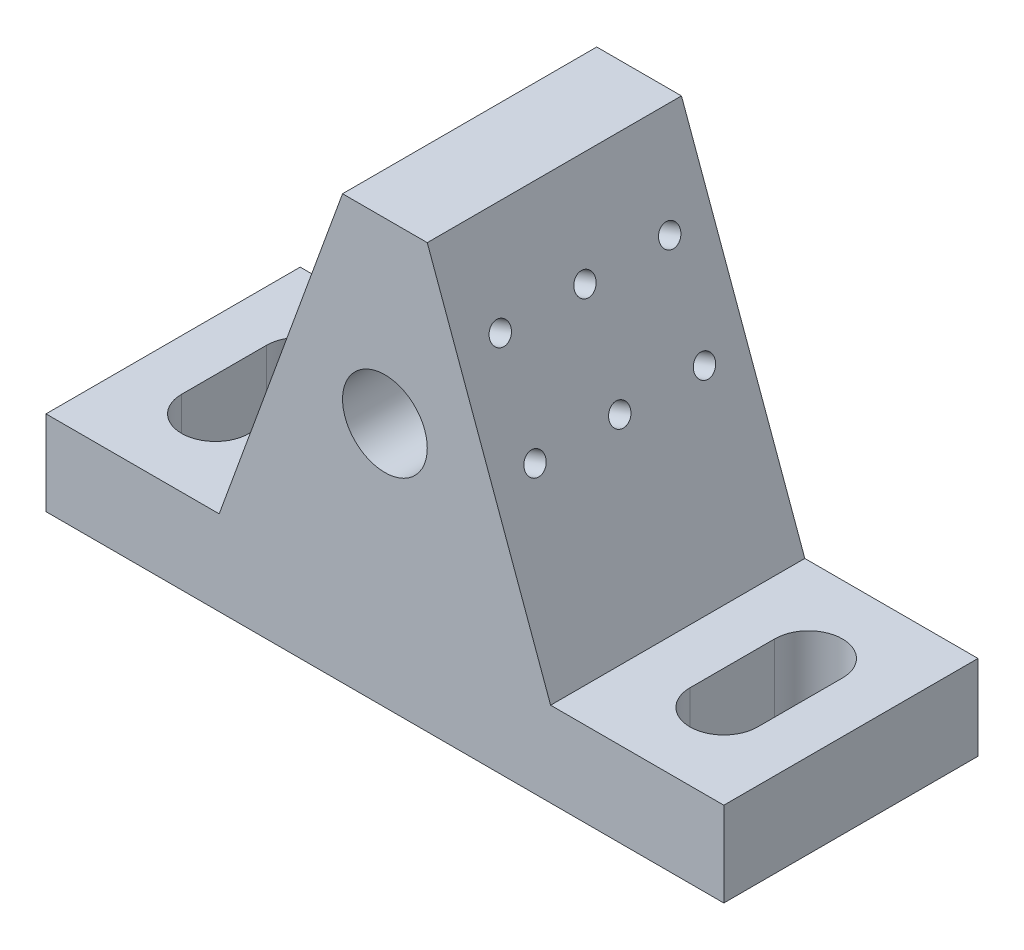
SolidWorks part; units mm, degrees
material "AISI 304"
ref_plane "Front Plane" through (0, 0, 0) normal (0, 0, 1) x (1, 0, 0)
ref_plane "Top Plane" through (0, 0, 0) normal (0, 1, 0) x (1, 0, 0)
ref_plane "Right Plane" through (0, 0, 0) normal (1, 0, 0) x (0, 0, -1)
sketch "Sketch2" plane through (0, 0, 0) normal (0, 0, 1) x (1, 0, 0)
  line L0 (0, 0) -> (0, 50) construction
  line L1 (-40, 0) -> (40, 0)
  line L2 (40, 0) -> (40, 10)
  line L3 (40, 10) -> (19.5588, 10)
  line L4 (19.5588, 10) -> (5, 50)
  line L5 (5, 50) -> (-5, 50)
  line L6 (-19.5588, 10) -> (-5, 50)
  line L7 (-40, 10) -> (-19.5588, 10)
  line L8 (-40, 0) -> (-40, 10)
  dimension "D1" = 10
  dimension "D2" = 10
  dimension "D3" = 110
  dimension "D4" = 80
  dimension "D5" = 50
extrude "Base Extrude" add sketch "Sketch2" along normal mid plane 30
sketch "Sketch4" plane through (0, 0, 0) normal (0, 1, 0) x (1, 0, 0)
  line L0 (30, -5) -> (30, 5) construction
  line L1 (26, -5) -> (26, 5)
  line L2 (34, -5) -> (34, 5)
  line L3 (40, 15) -> (19.5588, 15) construction
  arc A0 (26, -5) -> (34, -5) centre (30, -5) ccw
  arc A1 (34, 5) -> (26, 5) centre (30, 5) ccw
  point P2 (30, 0)
  dimension "D4" = 4
  dimension "D1" = 10
  dimension "D2" = 30
  dimension "D3" = 10
extrude "Slot Cut" cut sketch "Sketch4" along normal through all
mirror "Mirror1" about plane through (0, 0, 0) normal (1, 0, 0) of "Slot Cut"
sketch "Sketch5" plane through (0, 0, 15) normal (0, 0, 1) x (1, 0, 0)
  circle A0 centre (0, 29) radius 5
  dimension "D1" = 10
  dimension "D2" = 29
extrude "Guide Hole" cut sketch "Sketch5" against normal through all
hole_wizard "M3x0.5 Tapped Hole2" positions "3DSketch1" profile "Sketch10" tap size "M3x0.5" standard "ANSI Metric"
sketch3d "3DSketch1"
  line L0 (19.5588, 10, -15) -> (5, 50, -15) construction
  line L1 (19.5588, 10, 15) -> (19.5588, 10, -15) construction
  point P0 (12.7184, 28.7939, 10)
  dimension "D1" = 25
  dimension "D2" = 20
sketch "Sketch10" plane through (12.7184, 28.7939, 10) normal (0, 0, 1) x (-0.342, 0.9397, 0)
  line L0 (0, 0) -> (0, 8.2511)
  line L1 (0, 8.2511) -> (1.25, 7.5)
  line L2 (1.25, 7.5) -> (1.25, 0)
  line L5 (1.25, 0) -> (0, 0)
  line L10 (0, 8.2511) -> (-1.25, 7.5) construction
  line L11 (0, -6.35) -> (0, 107.95) construction
  dimension "Tap Drill Dia." = 2.5
  dimension "Tap Drill Depth" = 7.5
  dimension "Drill Angle" = 118
cosmetic thread "Hole Thread2" parameters "D1"=6, "D2"=3
pattern_linear "LPattern1" count 3 spacing 10 along (0, 0, -1) count 2 spacing 12 along (-0.342, 0.9397, 0) of "M3x0.5 Tapped Hole2"
cosmetic thread "Hole Thread3" parameters "D1"=6, "D2"=3
cosmetic thread "Hole Thread4" parameters "D1"=6, "D2"=3
cosmetic thread "Hole Thread5" parameters "D1"=6, "D2"=3
cosmetic thread "Hole Thread6" parameters "D1"=6, "D2"=3
cosmetic thread "Hole Thread7" parameters "D1"=6, "D2"=3
